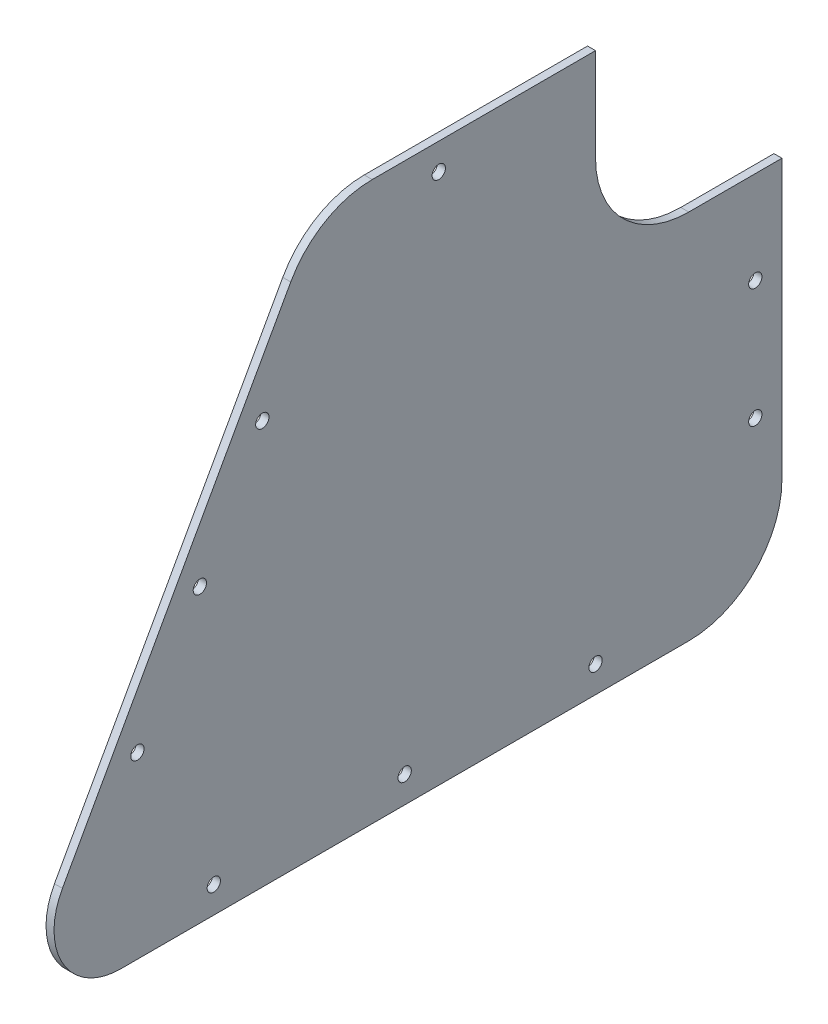
SolidWorks part; units mm, degrees
material "Acrylic (Medium-high impact)"
ref_plane "Front Plane" through (0, 0, 0) normal (0, 0, 1) x (1, 0, 0)
ref_plane "Top Plane" through (0, 0, 0) normal (0, 1, 0) x (1, 0, 0)
ref_plane "Right Plane" through (0, 0, 0) normal (1, 0, 0) x (0, 0, -1)
sketch "Sketch1" plane through (0, 0, 0) normal (1, 0, 0) x (0, 0, -1)
  line L0 (0, -1000) -> (0, 49000) construction
  line L1 (-1000, 0) -> (49000, 0) construction
  line L14 (-12.1885, 179.5) -> (106.6837, 179.5) construction
  line L15 (-29.6717, 169.2129) -> (-115.4252, 14.8564) construction
  line L16 (-106.6837, 0) -> (106.6837, 0) construction
  line L17 (126.6837, 20) -> (126.6837, 159.5) construction
  line L18 (-12.1885, 194.5) -> (106.6837, 194.5)
  line L19 (141.6837, 20) -> (141.6837, 159.5)
  line L20 (-106.6837, -15) -> (106.6837, -15)
  line L21 (-42.784, 176.4975) -> (-128.5376, 22.1411)
  arc A12 (-106.6837, 0) -> (-115.4252, 14.8564) centre (-106.6837, 10) cw construction
  arc A13 (106.6837, 0) -> (126.6837, 20) centre (106.6837, 20) ccw construction
  arc A14 (126.6837, 159.5) -> (106.6837, 179.5) centre (106.6837, 159.5) ccw construction
  arc A16 (-29.6717, 169.2129) -> (-12.1885, 179.5) centre (-12.1885, 159.5) cw construction
  arc A17 (141.6837, 159.5) -> (106.6837, 194.5) centre (106.6837, 159.5) ccw
  arc A18 (106.6837, -15) -> (141.6837, 20) centre (106.6837, 20) ccw
  arc A19 (-106.6837, -15) -> (-128.5376, 22.1411) centre (-106.6837, 10) cw
  arc A20 (-42.784, 176.4975) -> (-12.1885, 194.5) centre (-12.1885, 159.5) cw
  point P17 (47.2476, 179.5)
  point P18 (0, 0)
  dimension "D2" = 20
  dimension "D3" = 20
  dimension "D5" = 79.4361
  dimension "D1" = 10
  dimension "D4" = 20
  dimension "D6" = 213.3673
  dimension "D7" = 179.5
  dimension "D8" = 15
extrude "Boss-Extrude1" add sketch "Sketch1" along normal blind 3
sketch "Sketch2" plane through (3, 0, 0) normal (1, 0, 0) x (0, 0, -1)
  line L4 (-34.0424, 171.6411) -> (-119.796, 17.2846)
  line L5 (-34.0424, 171.6411) -> (-119.796, 17.2846) construction
  line L6 (-106.6837, -5) -> (106.6837, -5)
  line L7 (-106.6837, -5) -> (106.6837, -5) construction
  line L8 (131.6837, 20) -> (131.6837, 159.5)
  line L9 (131.6837, 20) -> (131.6837, 159.5) construction
  line L10 (106.6837, 184.5) -> (-12.1885, 184.5)
  line L11 (106.6837, 184.5) -> (-12.1885, 184.5) construction
  arc A4 (-12.1885, 184.5) -> (-34.0424, 171.6411) centre (-12.1885, 159.5) ccw
  arc A5 (-12.1885, 184.5) -> (-34.0424, 171.6411) centre (-12.1885, 159.5) ccw construction
  arc A6 (-119.796, 17.2846) -> (-106.6837, -5) centre (-106.6837, 10) ccw
  arc A7 (-119.796, 17.2846) -> (-106.6837, -5) centre (-106.6837, 10) ccw construction
  arc A8 (106.6837, -5) -> (131.6837, 20) centre (106.6837, 20) ccw
  arc A9 (106.6837, -5) -> (131.6837, 20) centre (106.6837, 20) ccw construction
  arc A10 (131.6837, 159.5) -> (106.6837, 184.5) centre (106.6837, 159.5) ccw
  arc A11 (131.6837, 159.5) -> (106.6837, 184.5) centre (106.6837, 159.5) ccw construction
  circle A32 centre (81.6837, 184.5) radius 2.5
  circle A33 centre (12.8115, 184.5) radius 2.5
  circle A34 centre (131.6837, 134.5) radius 2.5
  circle A35 centre (131.6837, 89.75) radius 2.5
  circle A44 centre (131.6837, 44.9999) radius 2.5
  circle A45 centre (71.6837, -5) radius 2.5
  circle A46 centre (0, -5) radius 2.5
  circle A47 centre (-71.6837, -5) radius 2.5
  circle A48 centre (-100.3703, 52.2509) radius 2.5
  circle A49 centre (-76.9192, 94.4629) radius 2.5
  circle A50 centre (-53.4682, 136.6748) radius 2.5
  dimension "D4" = 25
  dimension "D6" = 24.9999
  dimension "D7" = 35
  dimension "D8" = 35
  dimension "D9" = 40
  dimension "D10" = 40
  dimension "D2" = 5
  dimension "D5" = 25
  dimension "D3" = 25
  dimension "D1" = 10
extrude "Cut-Extrude1" cut sketch "Sketch2" against normal up to next
sketch "Sketch3" plane through (3, 0, 0) normal (1, 0, 0) x (0, 0, -1)
  line L0 (71.6837, 159.5) -> (71.6837, 194.5)
  line L1 (106.6837, 194.5) -> (-12.1885, 194.5) construction
  line L2 (106.6837, 124.5) -> (141.6837, 124.5)
  line L3 (141.6837, 20) -> (141.6837, 159.5) construction
  line L4 (141.6837, 124.5) -> (141.6837, 159.5)
  line L5 (106.6837, 194.5) -> (71.6837, 194.5)
  arc A1 (141.6837, 159.5) -> (106.6837, 194.5) centre (106.6837, 159.5) ccw construction
  arc A2 (71.6837, 159.5) -> (106.6837, 124.5) centre (106.6837, 159.5) ccw
  arc A3 (141.6837, 159.5) -> (106.6837, 194.5) centre (106.6837, 159.5) ccw
  point P5 (106.6837, 159.5)
extrude "Cut-Extrude2" cut sketch "Sketch3" against normal up to next
